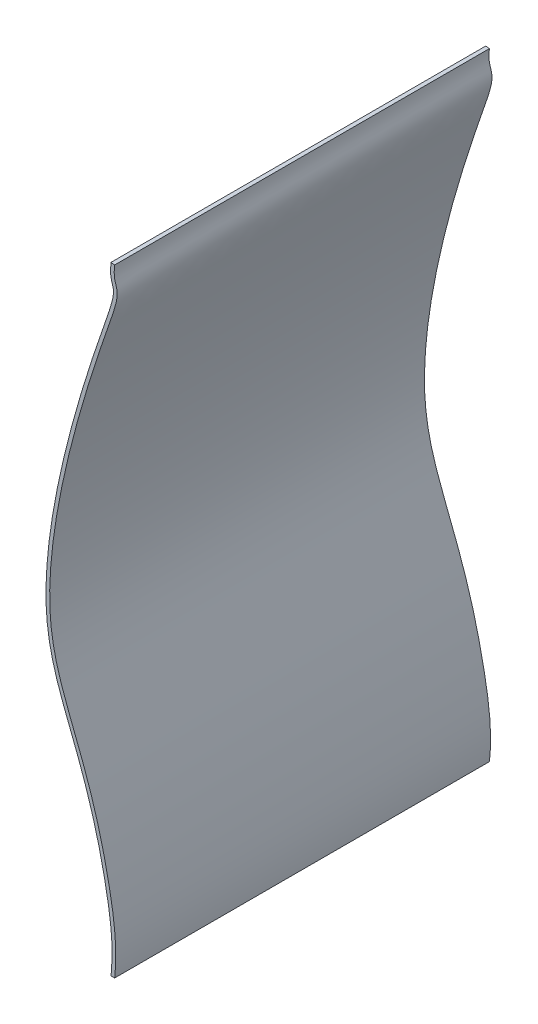
SolidWorks part; units mm, degrees
ref_plane "Front Plane" through (0, 0, 0) normal (0, 0, 1) x (1, 0, 0)
ref_plane "Top Plane" through (0, 0, 0) normal (0, 1, 0) x (1, 0, 0)
ref_plane "Right Plane" through (0, 0, 0) normal (1, 0, 0) x (0, 0, -1)
sketch "Sketch3" plane through (0, 0, 0) normal (0, 0, 1) x (1, 0, 0)
  line L0 (0, -1000) -> (0, 49000) construction
  line L1 (-1000, 0) -> (49000, 0) construction
  line L2 (-1000, 47.25) -> (0, 47.25) construction
  line L3 (-997.5622, 4.5) -> (49002.4378, 4.5) construction
  line L4 (-1000, 50.25) -> (49000, 50.25) construction
  line L5 (0, -885.9202) -> (0, 49114.0798) construction
  line L6 (-5.2592, -951.134) -> (-5.2592, 49048.866) construction
  line L7 (-1014.3991, 23.204) -> (48985.6009, 23.204) construction
  line L8 (0, 50.2836) -> (0.2981, 50.25)
  line L10 (0.302, 0) -> (0, 0)
  line L13 (0, 47.25) -> (49000, 47.25) construction
  spline S0 degree 3 poles (0, 50.2836) (-0.1837, 48.6532) (0.7347, 49.1493) (-3.4013, 37.7497) (-7.5447, 19.8669) (-1.8373, 14.8112) (0.2727, 2.1137) (0.0074, 0.07) (0, 0) knots 0 0 0 0 0.092047 0.141879 0.49832 0.877391 0.927559 1 1 1 1
  spline S1 degree 1 poles (0.2981, 50.25) (0.2983, -0.0316) knots 0 0 1 1 construction
  spline S2 degree 3 poles (0.2981, 50.25) (0.2848, 50.1317) (0.2636, 49.8751) (0.2622, 49.5147) (0.3053, 49.2042) (0.3887, 48.9481) (0.491, 48.6307) (0.5213, 48.1994) (0.3929, 47.4281) (-0.1344, 45.8566) (-0.9035, 43.6739) (-1.5948, 41.5528) (-2.2438, 39.4354) (-3.0319, 36.6569) (-3.8663, 33.2849) (-4.5849, 29.4956) (-4.9827, 26.0542) (-5.0207, 23.0605) (-4.668, 20.5969) (-4.0163, 18.3755) (-3.1482, 16.1339) (-2.1545, 13.618) (-1.3044, 11.088) (-0.6587, 8.6779) (-0.2067, 6.6511) (0.2143, 4.3536) (0.3933, 2.5198) (0.3931, 1.3259) (0.3603, 0.6094) (0.325, 0.2087) (0.3033, 0.0091) (0.3005, -0.0114) (0.2983, -0.0316) knots 0 0 0 0 0.007812 0.015623 0.031247 0.04687 0.062494 0.078117 0.093741 0.124988 0.156235 0.187481 0.218728 0.249975 0.312469 0.374963 0.437457 0.49995 0.562444 0.624938 0.687432 0.749926 0.812419 0.843666 0.874913 0.90616 0.937407 0.953031 0.968654 0.984277 0.992089 0.999901 0.999901 0.999901 0.999901 only from (0.2981, 50.25) to (0.302, 0)
  dimension "D1" = 50.25
  dimension "D2" = 3
  dimension "D3" = 4.5
  dimension "D4" = 0.3
extrude "Boss-Extrude3" add sketch "Sketch3" along normal blind 30.5
